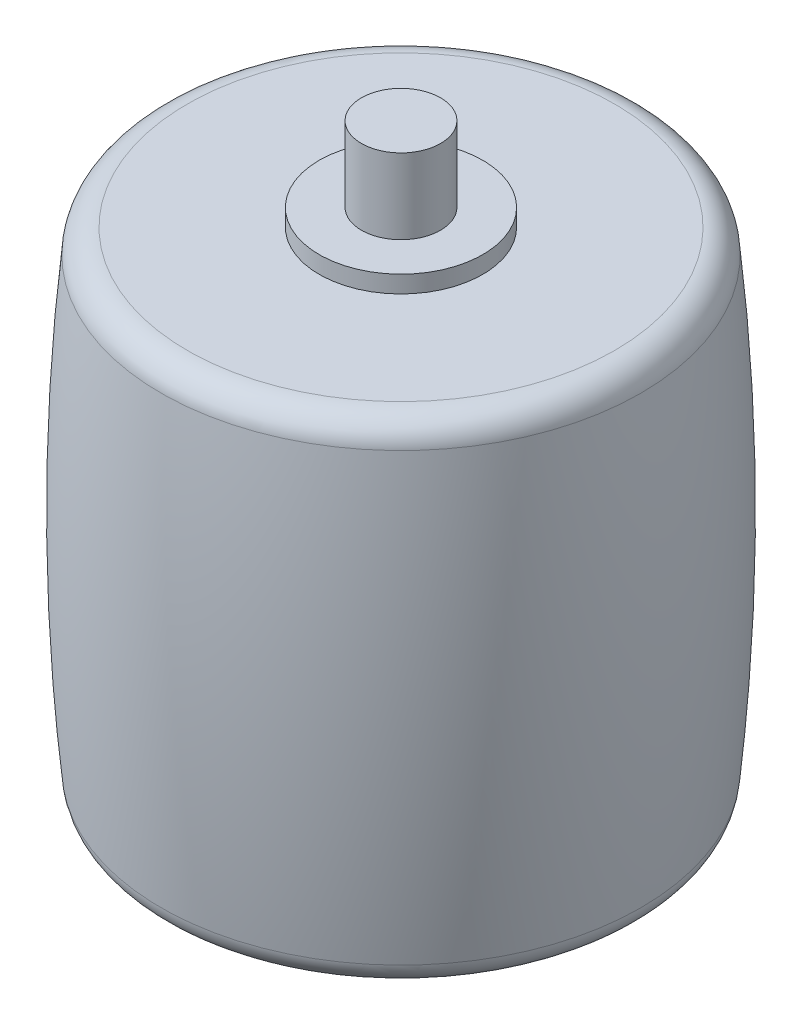
SolidWorks part; units mm, degrees
material "天然橡胶"
ref_plane "前视基准面" through (0, 0, 0) normal (0, 0, 1) x (1, 0, 0)
ref_plane "上视基准面" through (0, 0, 0) normal (0, 1, 0) x (1, 0, 0)
ref_plane "右视基准面" through (0, 0, 0) normal (1, 0, 0) x (0, 0, -1)
sketch "草图1" plane through (0, 0, 0) normal (0, 0, 1) x (1, 0, 0)
  line L0 (0, 12.85) -> (0, -12.85)
  line L1 (0, -12.85) -> (1.5, -12.85)
  line L2 (1.5, -12.85) -> (1.5, -10)
  line L3 (0, 12.85) -> (1.5, 12.85)
  line L4 (1.5, 12.85) -> (1.5, 10)
  line L5 (3.1, 9.35) -> (9, 9.35)
  line L6 (3.1, -9.35) -> (9, -9.35)
  line L7 (3.1, 9.35) -> (3.1, 10)
  line L8 (3.1, 10) -> (1.5, 10)
  line L9 (3.1, -9.35) -> (3.1, -10)
  line L10 (3.1, -10) -> (1.5, -10)
  arc A0 (9, 9.35) -> (9, -9.35) centre (-78.1725, 0) cw
  point P2 (9.5, 0)
  point P8 (0, 0)
  dimension "D2" = 9.5
  dimension "D1" = 25.7
  dimension "D3" = 18.7
  dimension "D4" = 1.5
  dimension "D5" = 9
  dimension "D7" = 20
  dimension "D8" = 3.1
revolve "旋转1" add sketch "草图1" angle 360 about L0
fillet "圆角1" radius 1 2 edges at (-9, -9.35, 0) (-9, 9.35, 0)
sketch "草图2" plane through (0, 0, 0) normal (0, 0, 1) x (1, 0, 0)
  line L0 (-1.5, -12.85) -> (1.5, -12.85) construction
  line L1 (1.5, -12.85) -> (1.5, -10) construction
  line L2 (-1.5, -10) -> (-1.5, -12.85) construction
  line L3 (-3.1, -9.35) -> (-3.1, -10) construction
  line L4 (-3.1, -10) -> (3.1, -10) construction
  line L5 (3.1, -10) -> (3.1, -9.35) construction
  line L6 (-8.0968, -9.35) -> (8.0968, -9.35) construction
  line L7 (-9.0922, -8.4463) -> (9.0922, -8.4463) construction
  line L8 (9.0922, 8.4463) -> (-9.0922, 8.4463) construction
  line L9 (8.0968, 9.35) -> (-8.0968, 9.35) construction
  line L10 (-3.1, 10) -> (-3.1, 9.35) construction
  line L11 (3.1, 9.35) -> (3.1, 10) construction
  line L12 (3.1, 10) -> (-3.1, 10) construction
  line L13 (1.5, 10) -> (1.5, 12.85) construction
  line L14 (-1.5, 12.85) -> (-1.5, 10) construction
  line L15 (1.5, 12.85) -> (-1.5, 12.85) construction
  line L16 (-1.5, -12.85) -> (1.5, -12.85)
  line L17 (1.5, -12.85) -> (1.5, -10)
  line L18 (-1.5, -10) -> (-1.5, -12.85)
  line L19 (-3.1, -9.35) -> (-3.1, -10)
  line L20 (-3.1, -10) -> (3.1, -10)
  line L21 (3.1, -10) -> (3.1, -9.35)
  line L22 (-8.0968, -9.35) -> (8.0968, -9.35)
  line L23 (-9.0922, -8.4463) -> (9.0922, -8.4463)
  line L24 (9.0922, 8.4463) -> (-9.0922, 8.4463)
  line L25 (8.0968, 9.35) -> (-8.0968, 9.35)
  line L26 (-3.1, 10) -> (-3.1, 9.35)
  line L27 (3.1, 9.35) -> (3.1, 10)
  line L28 (3.1, 10) -> (-3.1, 10)
  line L29 (1.5, 10) -> (1.5, 12.85)
  line L30 (-1.5, 12.85) -> (-1.5, 10)
  line L31 (1.5, 12.85) -> (-1.5, 12.85)
  arc A0 (8.0968, -9.35) -> (9.0922, -8.4463) centre (8.0968, -8.35) ccw construction
  arc A1 (-9.0922, -8.4463) -> (-8.0968, -9.35) centre (-8.0968, -8.35) ccw construction
  arc A2 (-9.0922, 8.4463) -> (-9.0922, -8.4463) centre (78.1725, 0) ccw construction
  arc A3 (9.0922, -8.4463) -> (9.0922, 8.4463) centre (-78.1725, 0) ccw construction
  arc A4 (9.0922, 8.4463) -> (8.0968, 9.35) centre (8.0968, 8.35) ccw construction
  arc A5 (-8.0968, 9.35) -> (-9.0922, 8.4463) centre (-8.0968, 8.35) ccw construction
  arc A6 (8.0968, -9.35) -> (9.0922, -8.4463) centre (8.0968, -8.35) ccw
  arc A7 (-9.0922, -8.4463) -> (-8.0968, -9.35) centre (-8.0968, -8.35) ccw
  arc A8 (-9.0922, 8.4463) -> (-9.0922, -8.4463) centre (78.1725, 0) ccw
  arc A9 (9.0922, -8.4463) -> (9.0922, 8.4463) centre (-78.1725, 0) ccw
  arc A10 (9.0922, 8.4463) -> (8.0968, 9.35) centre (8.0968, 8.35) ccw
  arc A11 (-8.0968, 9.35) -> (-9.0922, 8.4463) centre (-8.0968, 8.35) ccw
